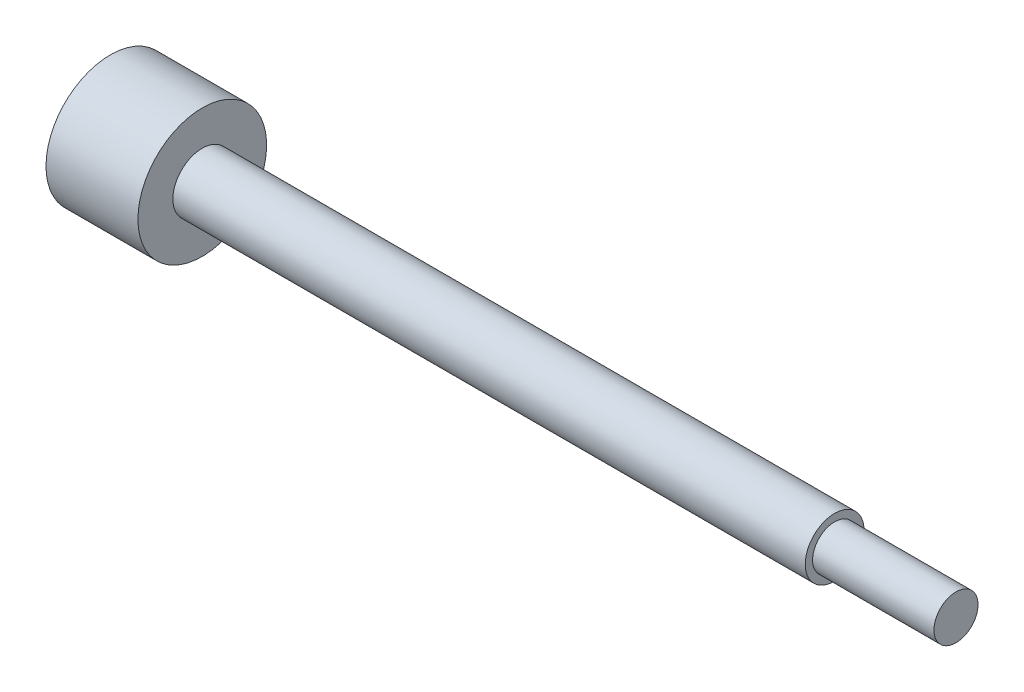
SolidWorks part; units mm, degrees
ref_plane "前视基准面" through (0, 0, 0) normal (0, 0, 1) x (1, 0, 0)
ref_plane "上视基准面" through (0, 0, 0) normal (0, 1, 0) x (1, 0, 0)
ref_plane "右视基准面" through (0, 0, 0) normal (1, 0, 0) x (0, 0, -1)
sketch "草图2" plane through (0, 0, 0) normal (0, 0, 1) x (1, 0, 0)
  line L0 (0, 0) -> (230, 0) construction
  line L1 (0, 0) -> (0, 17.5)
  line L2 (0, 17.5) -> (25, 17.5)
  line L3 (25, 17.5) -> (25, 8)
  line L4 (25, 8) -> (197, 8)
  line L5 (197, 8) -> (197, 6)
  line L6 (197, 6) -> (230, 6)
  line L7 (230, 6) -> (230, 0)
  line L8 (0, 0) -> (230, 0)
  dimension "D1" = 230
  dimension "D2" = 17.5
  dimension "D3" = 25
  dimension "D4" = 33
  dimension "D5" = 6
  dimension "D6" = 8
revolve "旋转1" add sketch "草图2" angle 360 about L0
